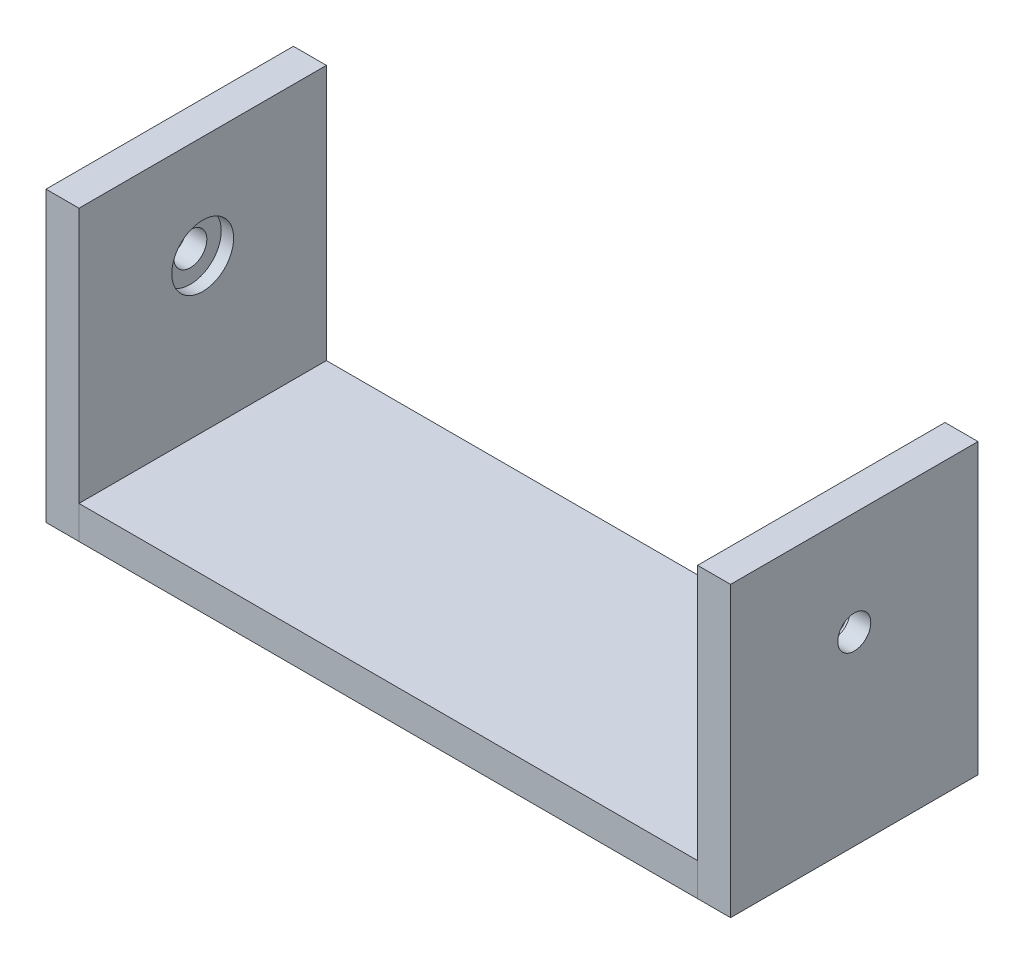
SolidWorks part; units mm, degrees
ref_plane "Front Plane" through (0, 0, 0) normal (0, 0, 1) x (1, 0, 0)
ref_plane "Top Plane" through (0, 0, 0) normal (0, 1, 0) x (1, 0, 0)
ref_plane "Right Plane" through (0, 0, 0) normal (1, 0, 0) x (0, 0, -1)
sketch "Sketch1" plane through (0, 0, 0) normal (0, 0, 1) x (1, 0, 0)
  line L1 (-75, -4) -> (75, -4)
  line L2 (-75, -4) -> (-75, 4)
  line L3 (-75, 4) -> (75, 4)
  line L4 (75, -4) -> (75, 4)
  line L5 (-75, -4) -> (75, 4) construction
  line L6 (-75, 4) -> (75, -4) construction
  point P0 (0, 0)
  dimension "D1" = 8
  dimension "D2" = 150
extrude "Boss-Extrude1" add sketch "Sketch1" along normal blind 60
sketch "Sketch2" plane through (75, 0, 0) normal (1, 0, 0) x (0, 0, -1)
  line L1 (-60, -4) -> (0, -4)
  line L2 (-60, -4) -> (-60, 66)
  line L3 (-60, 66) -> (0, 66)
  line L4 (0, -4) -> (0, 66)
  dimension "D1" = 60
  dimension "D2" = 70
extrude "Boss-Extrude2" add sketch "Sketch2" along normal blind 8 separate body
sketch "Sketch3" plane through (-75, 0, 0) normal (-1, 0, 0) x (0, 0, 1)
  line L4 (60, -4) -> (60, 66)
  line L5 (0, -4) -> (60, -4)
  line L6 (0, 66) -> (0, -4)
  line L7 (60, 66) -> (0, 66)
  line L8 (60, -4) -> (60, 66)
  line L9 (0, -4) -> (60, -4)
  line L10 (0, 66) -> (0, -4)
  line L11 (60, 66) -> (0, 66)
  dimension "D1" = 0
extrude "Boss-Extrude3" add sketch "Sketch3" along normal blind 8 separate body
sketch "Sketch4" plane through (83, 0, 0) normal (1, 0, 0) x (0, 0, -1)
  line L0 (0, 66) -> (-60, 66) construction
  circle A0 centre (-30, 41) radius 4
  dimension "D1" = 8
  dimension "D2" = 25
  dimension "D3" = 30
extrude "Cut-Extrude1" cut sketch "Sketch4" against normal through all
sketch "Sketch5" plane through (75, 0, 0) normal (-1, 0, 0) x (0, 0, 1)
  circle A0 centre (30, 41) radius 7.5
  dimension "D1" = 15
extrude "Cut-Extrude2" cut sketch "Sketch5" against normal blind 3
sketch "Sketch6" plane through (-75, 0, 0) normal (1, 0, 0) x (0, 0, -1)
  circle A0 centre (-30, 41) radius 7.5
  dimension "D1" = 15
extrude "Cut-Extrude3" cut sketch "Sketch6" against normal blind 3
